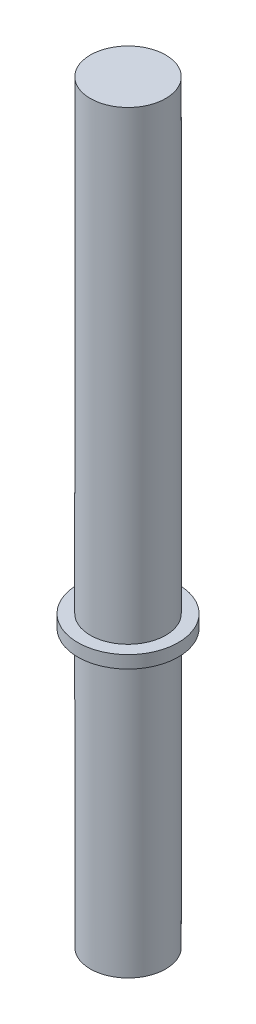
SolidWorks part; units mm, degrees
ref_plane "前视基准面" through (0, 0, 0) normal (0, 0, 1) x (1, 0, 0)
ref_plane "上视基准面" through (0, 0, 0) normal (0, 1, 0) x (1, 0, 0)
ref_plane "右视基准面" through (0, 0, 0) normal (1, 0, 0) x (0, 0, -1)
sketch "草图1" plane through (0, 0, 0) normal (0, 1, 0) x (1, 0, 0)
  circle A0 centre (0, 0) radius 1.5
extrude "凸台-拉伸1" add sketch "草图1" along normal blind 30
sketch "草图2" plane through (0, 0, 0) normal (0, -1, 0) x (1, 0, 0)
  circle A0 centre (0, 0) radius 1.5
  circle A1 centre (0, 0) radius 2
extrude "凸台-拉伸2" add sketch "草图2" against normal blind 0.5 from offset 11
